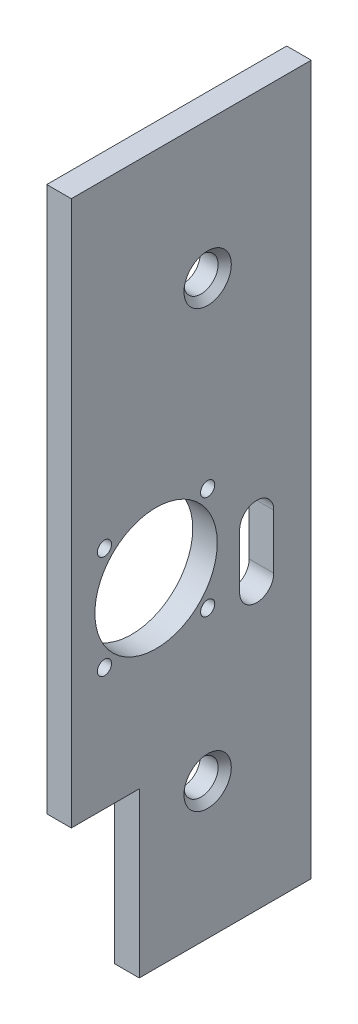
SolidWorks part; units mm, degrees
material "6061-T6 (SS)"
ref_plane "Front Plane" through (0, 0, 0) normal (1, 0, 0) x (0, 1, 0)
ref_plane "Top Plane" through (0, 0, 0) normal (0, 0, 1) x (0, 1, 0)
ref_plane "Right Plane" through (0, 0, 0) normal (0, 1, 0) x (-1, 0, 0)
sketch "Sketch1" plane through (0, 0, 0) normal (1, 0, 0) x (0, 1, 0)
  line L0 (-99.0988, 12.7) -> (-86.3988, 12.7) construction
  line L1 (0, 0) -> (-165.1, 0)
  line L2 (0, 0) -> (0, 55.88)
  line L3 (0, 55.88) -> (-165.1, 55.88)
  line L4 (-165.1, 0) -> (-165.1, 55.88)
  line L9 (-99.0988, 16.6687) -> (-86.3988, 16.6687)
  line L10 (-99.0988, 8.7312) -> (-86.3988, 8.7312)
  line L12 (-74.378, 24.1168) -> (-98.4197, 24.1168) construction
  line L13 (-74.378, 24.1168) -> (-74.378, 48.1585) construction
  line L14 (-74.378, 48.1585) -> (-98.4197, 48.1585) construction
  line L15 (-98.4197, 24.1168) -> (-98.4197, 48.1585) construction
  line L16 (-74.378, 24.1168) -> (-98.4197, 48.1585) construction
  line L17 (-74.378, 48.1585) -> (-98.4197, 24.1168) construction
  line L21 (-165.1, 55.88) -> (-155.6671, 55.88) construction
  line L22 (-165.1, 55.88) -> (-165.1, 46.99) construction
  line L26 (-165.1, 55.88) -> (-126.9378, 55.88)
  line L27 (-165.1, 55.88) -> (-165.1, 40.0526)
  line L28 (-165.1, 40.0526) -> (-126.9378, 40.0526)
  line L29 (-126.9378, 55.88) -> (-126.9378, 40.0526)
  circle A0 centre (-133.35, 24.13) radius 3.9751
  circle A1 centre (-31.9024, 24.13) radius 3.9751
  arc A2 (-99.0988, 16.6687) -> (-99.0988, 8.7312) centre (-99.0988, 12.7) ccw
  arc A3 (-86.3988, 8.7312) -> (-86.3988, 16.6687) centre (-86.3988, 12.7) ccw
  circle A4 centre (-86.3988, 36.1377) radius 14.25
  circle A6 centre (-31.9024, 24.13) radius 27.305 construction
  circle A7 centre (-133.35, 24.13) radius 27.305 construction
  point P15 (-92.7488, 12.7)
  dimension "D1" = 7.9502
  dimension "D2" = 3.9688
  dimension "D5" = 28.5
  dimension "D13" = 54.61
  dimension "D14" = 54.61
  dimension "D3" = 12.7
  dimension "D6" = 55.88
  dimension "D9" = 24.13
  dimension "D10" = 31.75
  dimension "D11" = 31.9024
  dimension "D12" = 165.1
  dimension "D22" = 12.7
  dimension "D4" = 34
extrude "Boss-Extrude1" add sketch "Sketch1" along normal blind 5.715 contours L3 L29 L28 L4 L1 L2 A4 A3 L10 A2 L9 A1 A0
hole_wizard "M4x0.7 Tapped Hole1" positions "Sketch5" profile "Sketch6" tap size "M4x0.7" standard "ANSI Metric" end condition up to next
sketch "Sketch5" plane through (5.715, 0, 0) normal (1, 0, 0) x (0, 0, -1)
  point P0 (-48.1585, -74.378)
  point P3 (-24.1168, -74.378)
  point P6 (-24.1168, -98.4197)
  point P9 (-48.1585, -98.4197)
sketch "Sketch6" plane through (5.715, -74.378, 48.1585) normal (0, 1, 0) x (0, 0, -1)
  line L0 (0, 0) -> (0, 5.715)
  line L1 (0, 5.715) -> (1.65, 5.715)
  line L2 (1.65, 5.715) -> (1.65, 0)
  line L5 (1.65, 0) -> (0, 0)
  line L11 (0, -6.35) -> (0, 107.95) construction
  dimension "Thru Tap Drill Dia." = 3.3
  dimension "Thru Tap Drill Depth" = 5.715
cosmetic thread "Hole Thread5" parameters "D2"=4
cosmetic thread "Hole Thread6" parameters "D2"=4
cosmetic thread "Hole Thread7" parameters "D2"=4
cosmetic thread "Hole Thread8" parameters "D2"=4
ref_plane "Plane1" through (12.7, 0, 0) normal (1, 0, 0) x (0, 1, 0)
sketch "Pully" plane through (12.7, 0, 0) normal (1, 0, 0) x (0, 1, 0)
  line L0 (-99.0988, 12.7) -> (-86.3988, 12.7) construction
  line L1 (-132.9499, 45.1262) -> (-86.2445, 44.2362)
  line L2 (-133.35, 3.13) -> (-31.9024, 3.13)
  line L3 (-44.4982, 40.9331) -> (-88.9401, 7.619)
  line L4 (-96.6864, 17.6818) -> (-81.3761, 29.783)
  line L5 (-132.9499, 45.1262) -> (-133.35, 24.13) construction
  line L6 (-133.35, 24.13) -> (-133.35, 3.13) construction
  line L7 (-86.2445, 44.2362) -> (-86.3988, 36.1377) construction
  line L8 (-86.3988, 36.1377) -> (-81.3761, 29.783) construction
  line L9 (-44.4982, 40.9331) -> (-31.9024, 24.13) construction
  line L10 (-31.9024, 24.13) -> (-31.9024, 3.13) construction
  line L11 (-96.6864, 17.6818) -> (-92.7488, 12.7) construction
  line L12 (-92.7488, 12.7) -> (-88.9401, 7.619) construction
  circle A0 centre (-133.35, 24.13) radius 21
  circle A1 centre (-92.7488, 12.7) radius 6.35
  circle A2 centre (-86.3988, 36.1377) radius 8.1
  circle A3 centre (-31.9024, 24.13) radius 21
  dimension "D2" = 12.7
  dimension "D3" = 16.2
  dimension "D1" = 42
  dimension "D4" = 181.092
  dimension "D5" = 216.856
  dimension "D6" = 140.586
  dimension "D7" = 178.533
chamfer "Chamfer1" distance 1.5367 angle 45 2 edges at (5.715, -31.9024, 20.1549) (5.715, -133.35, 20.1549)
equation "\"D2@Sketch1\"=0.5*0.3125"
equation "\"D1@Pully\"=42mm"
equation "\"D3@Pully\"=16.2mm"
equation "\"D4@Sketch1\"=34mm"
equation "\"D5@Sketch1\"=28.5mm"
